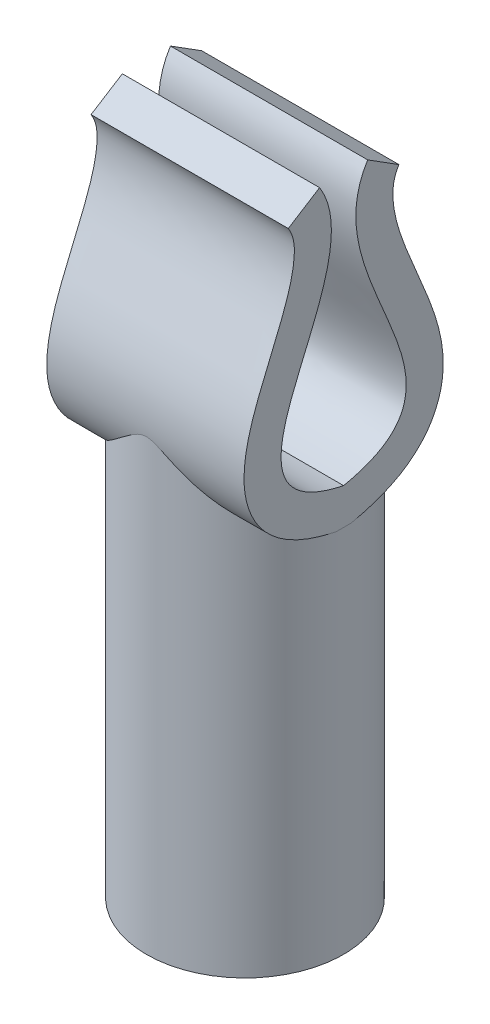
SolidWorks part; units mm, degrees
ref_plane "Front Plane" through (0, 0, 0) normal (0, 0, 1) x (1, 0, 0)
ref_plane "Top Plane" through (0, 0, 0) normal (0, 1, 0) x (1, 0, 0)
ref_plane "Right Plane" through (0, 0, 0) normal (1, 0, 0) x (0, 0, -1)
sketch "Sketch2" plane through (0, 0, 0) normal (0, 1, 0) x (1, 0, 0)
  line L1 (-2.4, 2.4) -> (2.4, 2.4)
  line L2 (-2.4, 2.4) -> (-2.4, -2.4)
  line L3 (-2.4, -2.4) -> (2.4, -2.4)
  line L4 (2.4, 2.4) -> (2.4, -2.4)
  line L5 (-2.4, 2.4) -> (2.4, -2.4) construction
  line L6 (-2.4, -2.4) -> (2.4, 2.4) construction
  point P0 (0, 0)
  dimension "D1" = 4.8
extrude "Boss-Extrude1" add sketch "Sketch2" along normal blind 10
sketch "Sketch3" plane through (0, 0, 0) normal (1, 0, 0) x (0, 0, -1)
  line L0 (0, 0) -> (0, 17) construction
  line L1 (-2.4, 10) -> (2.4, 10) construction
  line L6 (0.9753, 19.4549) -> (2.2442, 18.6549)
  line L7 (0, 8.5) -> (0, 7.0316)
  line L8 (0, 7.0316) -> (0.3065, 7.0316)
  spline S0 degree 3 poles (0, 8.5) (6.3056, 9.8162) (-1.4231, 15.6507) (0.9753, 19.4549) knots 0 0 0 0 1 1 1 1
  spline S1 degree 1 poles (0.3065, 7.0316) (2.2442, 18.6549) knots 0 0 1 1 construction
  spline S2 degree 3 poles (0.3065, 7.0316) (0.53, 7.0783) (0.9843, 7.1901) (1.7886, 7.4654) (2.6822, 7.9377) (3.5301, 8.7929) (3.9938, 9.8695) (4.0733, 10.9201) (3.8854, 12.187) (3.3601, 13.618) (2.636, 15.2524) (2.0799, 16.7588) (1.9375, 17.933) (2.0963, 18.4203) (2.2442, 18.6549) knots 0 0 0 0 0.03125 0.0625 0.125 0.1875 0.25 0.3125 0.375 0.5 0.625 0.75 0.875 1 1 1 1
  dimension "D1" = 7
  dimension "D2" = 0.5
  dimension "D3" = 1.8911
  dimension "D4" = 7.5639
  dimension "D5" = 0.9753
  dimension "D6" = 1.5
extrude "Boss-Extrude2" add sketch "Sketch3" along normal mid plane 8
mirror "Mirror2" about plane through (0, 0, 0) normal (0, 0, 1) of "Boss-Extrude2"
sketch "Sketch4" plane through (-4, 0, 0) normal (-1, 0, 0) x (0, 0, 1)
  line L0 (-2.4, 10) -> (2.4, 10) construction
  line L1 (-2.4, 10) -> (2.4, 10)
  spline S0 degree 3 poles (1931.2425, 528.0278) (-1972.8162, -550.3104) (1976.4973, 553.627) (-1954.104, -424.5445) knots -2.970631 -2.970631 -2.970631 -2.970631 5.696973 5.696973 5.696973 5.696973 only from (0, 8.5) to (-2.4, 10) construction
  spline S1 degree 3 poles (0, 8.5) (-1.4187, 8.7961) (-2.127, 9.321) (-2.4, 10) knots 0.775005 0.775005 0.775005 0.775005 1 1 1 1
  spline S2 degree 3 poles (1950.8736, -423.7406) (-1974.319, 553.0186) (1971.7183, -550.007) (-1931.2014, 528.0164) knots -3.919592 -3.919592 -3.919592 -3.919592 4.745606 4.745606 4.745606 4.745606 only from (0.9753, 19.4549) to (0, 8.5) construction
  spline S3 degree 3 poles (0.9753, 19.4549) (-1.4231, 15.6507) (6.3056, 9.8162) (0, 8.5) knots 0 0 0 0 1 1 1 1
  spline M3 degree 3 poles (0.9753, 19.4549) (-1.4231, 15.6507) (6.3056, 9.8162) (0, 8.5) knots 0 0 0 0 1 1 1 1
  spline M4 degree 3 poles (0, 8.5) (-6.3056, 9.8162) (1.4231, 15.6507) (-0.9753, 19.4549) knots 0 0 0 0 1 1 1 1
extrude "Cut-Extrude2" cut sketch "Sketch4" against normal blind 13 contours L1 M4 M3
chamfer "Chamfer2" distance 1 angle 45 4 edges at (0, 0, -2.4) (-2.4, 0, 0) (0, 0, 2.4) (2.4, 0, 0)
sketch "Sketch7" plane through (4, 0, 0) normal (1, 0, 0) x (0, 0, -1)
  line L0 (-0.3065, 7.0316) -> (0.3065, 7.0316) construction
  line L1 (-0.3065, 7.0316) -> (0.3065, 7.0316)
  line L2 (-2.4, 7.8182) -> (-2.4, 0)
  line L3 (-2.4, 0) -> (2.4, 0)
  line L4 (2.4, 0) -> (2.4, 7.8182)
  spline S0 degree 3 poles (-1961.6829, 397.5514) (53.0699, 17.1029) (8.8715, 3.817) (-20.5291, 13.8793) (29.1008, 99.6098) (964.1986, 1758.5714) knots -1.531728 -1.531728 -1.531728 -1.531728 0.03125 0.0625 3.037542 3.037542 3.037542 3.037542 only from (-0.3065, 7.0316) to (-2.4, 7.8182) construction
  spline S1 degree 3 poles (-0.3065, 7.0316) (-0.53, 7.0783) (-0.9843, 7.1901) (-1.6889, 7.4313) (-2.1457, 7.6572) (-2.4, 7.8182) knots 0 0 0 0 0.03125 0.0625 0.109507 0.109507 0.109507 0.109507
  spline S2 degree 3 poles (1961.6829, 397.5514) (-53.0699, 17.1029) (-8.8715, 3.817) (20.5291, 13.8793) (-29.1008, 99.6098) (-964.1986, 1758.5714) knots -1.531728 -1.531728 -1.531728 -1.531728 0.03125 0.0625 3.037542 3.037542 3.037542 3.037542 only from (0.3065, 7.0316) to (2.4, 7.8182) construction
  spline S3 degree 3 poles (0.3065, 7.0316) (0.53, 7.0783) (0.9843, 7.1901) (1.6889, 7.4313) (2.1457, 7.6572) (2.4, 7.8182) knots 0 0 0 0 0.03125 0.0625 0.109507 0.109507 0.109507 0.109507
extrude "Cut-Extrude3" cut sketch "Sketch7" against normal blind 10
ref_plane "Plane1" through (0, -7.9684, 0) normal (0, -1, 0) x (-1, 0, 0)
sketch "Sketch8" plane through (0, -7.9684, 0) normal (0, -1, 0) x (-1, 0, 0)
  circle A0 centre (0, 0) radius 4
  dimension "D1" = 8
extrude "Boss-Extrude4" add sketch "Sketch8" against normal up to next
sketch "Sketch9" plane through (0, -7.9684, 0) normal (0, -1, 0) x (1, 0, 0)
  circle A0 centre (0, 0) radius 3.15
  dimension "D1" = 6.3
extrude "Cut-Extrude4" cut sketch "Sketch9" against normal blind 3
equation "\"W\"=4.8"
equation "\"D1@Sketch2\"=\"W\""
